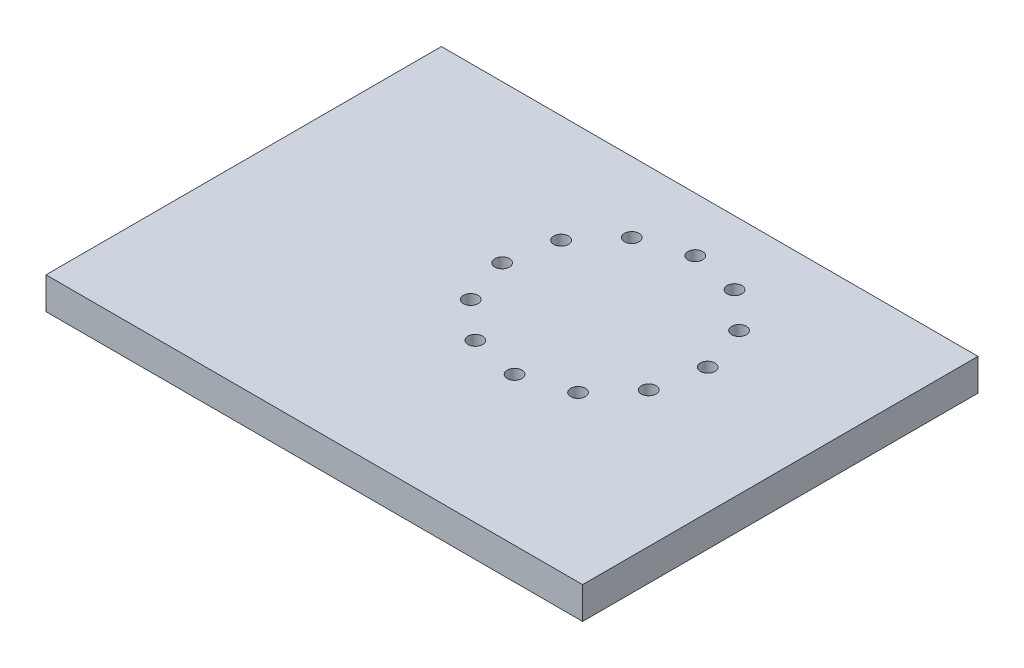
SolidWorks part; units mm, degrees
material "6061-T6 (SS)"
ref_plane "X-Y Datum" through (0, 0, 0) normal (0, 0, 1) x (1, 0, 0)
ref_plane "X-Z Datum" through (0, 0, 0) normal (0, 1, 0) x (1, 0, 0)
ref_plane "Y-Z Datum" through (0, 0, 0) normal (1, 0, 0) x (0, 0, -1)
sketch "Sketch1" plane through (0, 0, 0) normal (0, 1, 0) x (1, 0, 0)
  line L1 (0, 0) -> (241.3, 0)
  line L2 (0, 0) -> (0, 177.8)
  line L3 (0, 177.8) -> (241.3, 177.8)
  line L4 (241.3, 0) -> (241.3, 177.8)
  dimension "D1" = 177.8
  dimension "D2" = 241.3
extrude "Boss-Extrude1" add sketch "Sketch1" along normal blind 14.351
sketch "Sketch2" plane through (0, 14.351, 0) normal (0, 1, 0) x (1, 0, 0)
  circle A0 centre (231.0696, 166.4926) radius 3.3 construction
  circle A1 centre (231.0696, 166.4926) radius 3.3
  circle A2 centre (227.4115, 61.3687) radius 3.3 construction
  circle A3 centre (227.4115, 61.3687) radius 3.3
  circle A4 centre (26.2358, 156.1144) radius 3.3 construction
  circle A5 centre (26.2358, 156.1144) radius 3.3
sketch "Sketch3" plane through (0, 14.351, 0) normal (0, 1, 0) x (1, 0, 0)
  circle A0 centre (180.3092, 90.7216) radius 3.3 construction
  circle A1 centre (184.7298, 112.8007) radius 3.3 construction
  circle A2 centre (177.5186, 134.132) radius 3.3 construction
  circle A3 centre (160.6079, 148.9999) radius 3.3 construction
  circle A4 centre (138.5288, 153.4205) radius 3.3 construction
  circle A5 centre (117.1975, 146.2093) radius 3.3 construction
  circle A6 centre (102.3296, 129.2986) radius 3.3 construction
  circle A7 centre (97.909, 107.2196) radius 3.3 construction
  circle A8 centre (105.1202, 85.8882) radius 3.3 construction
  circle A9 centre (122.0309, 71.0203) radius 3.3 construction
  circle A10 centre (165.4413, 73.8109) radius 3.3 construction
  circle A11 centre (144.1099, 66.5997) radius 3.3 construction
  circle A12 centre (180.3092, 90.7216) radius 3.3
  circle A13 centre (184.7298, 112.8007) radius 3.3
  circle A14 centre (177.5186, 134.132) radius 3.3
  circle A15 centre (160.6079, 148.9999) radius 3.3
  circle A16 centre (138.5288, 153.4205) radius 3.3
  circle A17 centre (117.1975, 146.2093) radius 3.3
  circle A18 centre (102.3296, 129.2986) radius 3.3
  circle A19 centre (97.909, 107.2196) radius 3.3
  circle A20 centre (105.1202, 85.8882) radius 3.3
  circle A21 centre (122.0309, 71.0203) radius 3.3
  circle A22 centre (165.4413, 73.8109) radius 3.3
  circle A23 centre (144.1099, 66.5997) radius 3.3
extrude "Cut-Extrude1" cut sketch "Sketch3" against normal through all
